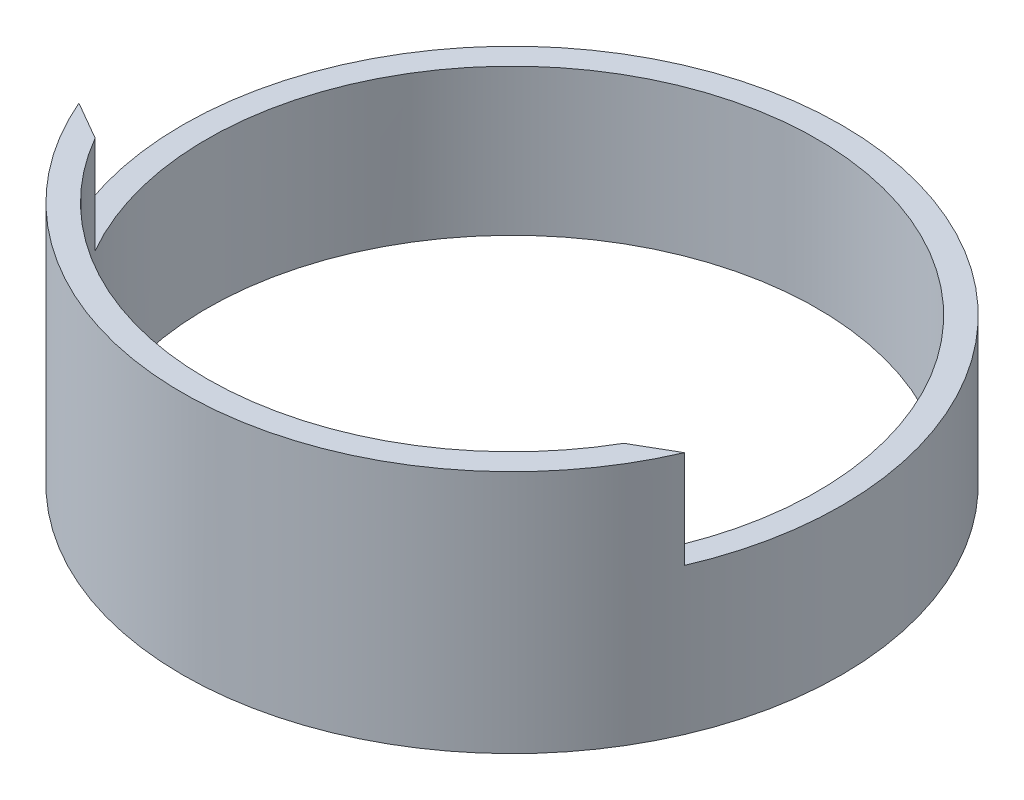
SolidWorks part; units mm, degrees
ref_plane "Front Plane" through (0, 0, 0) normal (0, 0, 1) x (1, 0, 0)
ref_plane "Top Plane" through (0, 0, 0) normal (0, 1, 0) x (1, 0, 0)
ref_plane "Right Plane" through (0, 0, 0) normal (1, 0, 0) x (0, 0, -1)
sketch "Sketch1" plane through (0, 0, 0) normal (0, 1, 0) x (1, 0, 0)
  circle A0 centre (0, 0) radius 12.5
  circle A1 centre (0, 0) radius 13.5
  dimension "D1" = 25
  dimension "D2" = 27
extrude "Boss-Extrude1" add sketch "Sketch1" along normal blind 10
sketch "Sketch2" plane through (0, 10, 0) normal (0, 1, 0) x (1, 0, 0)
  line L0 (-45.0333, 13.5) -> (0, -12.5)
  line L1 (0, -12.5) -> (45.0333, 13.5)
  line L2 (45.0333, 13.5) -> (-45.0333, 13.5)
  line L3 (0, 13.5) -> (0, -12.5) construction
  circle A0 centre (0, 0) radius 12.5 construction
  circle A1 centre (0, 0) radius 13.5 construction
  point P6 (0, -12.5)
  point P10 (38.2829, 13.5)
  dimension "D1" = 120
extrude "Cut-Extrude1" cut sketch "Sketch2" against normal blind 4
